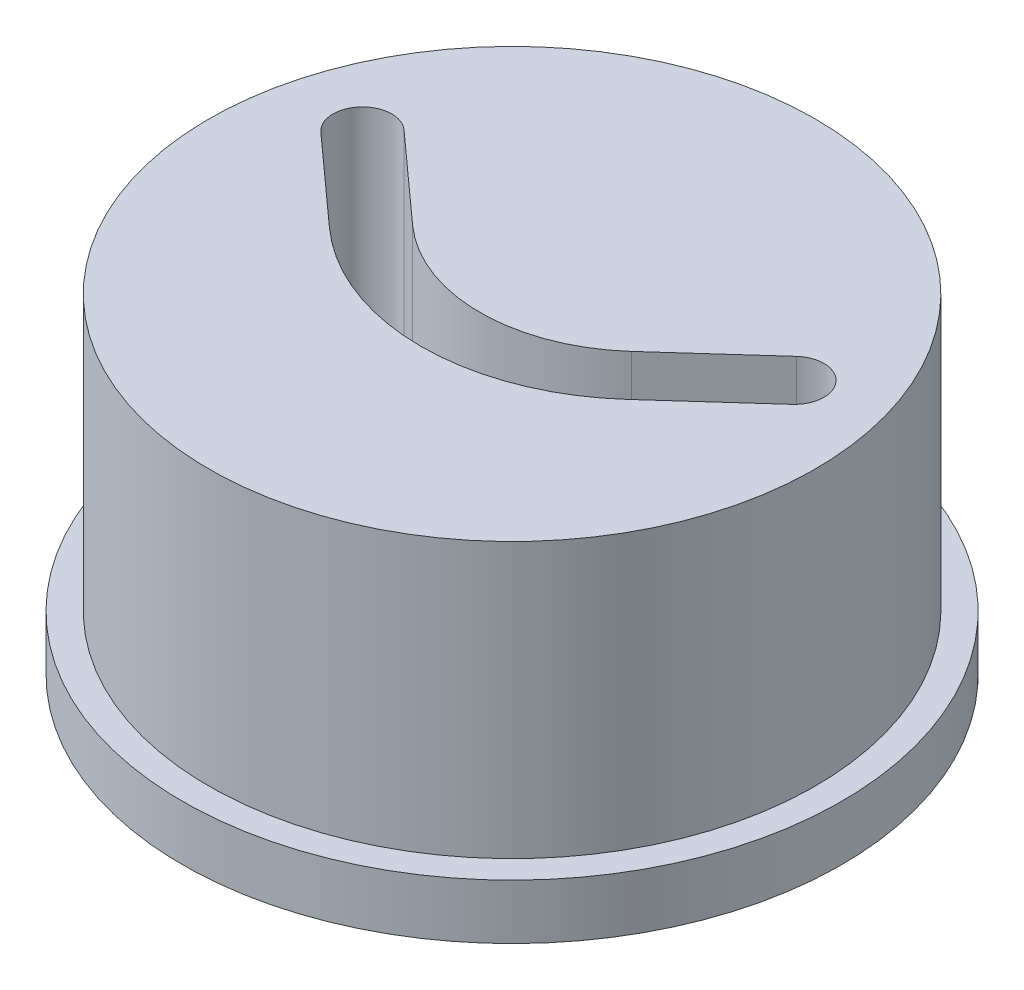
SolidWorks part; units mm, degrees
ref_plane "Front Plane" through (0, 0, 0) normal (0, 0, 1) x (1, 0, 0)
ref_plane "Top Plane" through (0, 0, 0) normal (0, 1, 0) x (1, 0, 0)
ref_plane "Right Plane" through (0, 0, 0) normal (1, 0, 0) x (0, 0, -1)
sketch "Sketch2" plane through (0, 0, 0) normal (0, 1, 0) x (1, 0, 0)
  line L0 (-6.985, 0) -> (6.985, 0) construction
  line L10 (0, 6.985) -> (0, -6.985) construction
  line L13 (0, -6.985) -> (0, 0) construction
  line L14 (-13.081, 3.175) -> (13.081, 3.175) construction
  line L15 (0, -4.445) -> (0, 3.175) construction
  line L16 (-13.081, 3.175) -> (-8.0591, -1.3498)
  line L17 (13.081, 3.175) -> (8.0591, -1.3498)
  line L18 (-11.8908, 4.4959) -> (-6.8689, -0.0289)
  line L19 (11.8908, 4.4959) -> (6.8689, -0.0289)
  line L21 (-12.4859, 3.8355) -> (12.4859, 3.8355) construction
  circle A0 centre (0, 0) radius 17.526
  arc A9 (-8.0591, -1.3498) -> (8.0591, -1.3498) centre (0, 7.5946) ccw
  arc A10 (-13.081, 3.175) -> (-11.8908, 4.4959) centre (-12.4859, 3.8355) cw
  arc A11 (-6.8689, -0.0289) -> (6.8689, -0.0289) centre (0, 7.5946) ccw
  arc A12 (11.8908, 4.4959) -> (13.081, 3.175) centre (12.4859, 3.8355) cw
  point P13 (12.2811, 12.5034)
  point P36 (0, 3.175)
  point P37 (-33.8663, 15.7634)
  point P42 (0, -4.445)
  point P47 (0, 3.175)
  dimension "D1" = 35.052
  dimension "D4" = 24.9718
  dimension "D9" = 12.0396
  dimension "D11" = 0.889
  dimension "D12" = 10.2616
  dimension "D3" = 3.175
  dimension "D10" = 6.7597
extrude "Boss-Extrude1" add sketch "Sketch2" along normal blind 19.05
sketch "Sketch14" plane through (0, 19.05, 0) normal (0, 1, 0) x (1, 0, 0)
  line L37 (8.6032, -1.9537) -> (13.6251, 2.5712)
  line L38 (11.3468, 5.0997) -> (6.3249, 0.5749)
  line L39 (-6.3249, 0.5749) -> (-11.3468, 5.0997)
  line L40 (-13.6251, 2.5712) -> (-8.6032, -1.9537)
  line L41 (8.6032, -1.9537) -> (13.6251, 2.5712)
  line L42 (11.3468, 5.0997) -> (6.3249, 0.5749)
  line L43 (-6.3249, 0.5749) -> (-11.3468, 5.0997)
  line L44 (-13.6251, 2.5712) -> (-8.6032, -1.9537)
  arc A43 (13.6251, 2.5712) -> (11.3468, 5.0997) centre (12.4859, 3.8355) ccw
  arc A44 (-6.3249, 0.5749) -> (6.3249, 0.5749) centre (0, 7.5946) ccw
  arc A45 (-11.3468, 5.0997) -> (-13.6251, 2.5712) centre (-12.4859, 3.8355) ccw
  arc A46 (-8.6032, -1.9537) -> (8.6032, -1.9537) centre (0, 7.5946) ccw
  arc A47 (13.6251, 2.5712) -> (11.3468, 5.0997) centre (12.4859, 3.8355) ccw
  arc A48 (-6.3249, 0.5749) -> (6.3249, 0.5749) centre (0, 7.5946) ccw
  arc A49 (-11.3468, 5.0997) -> (-13.6251, 2.5712) centre (-12.4859, 3.8355) ccw
  arc A50 (-8.6032, -1.9537) -> (8.6032, -1.9537) centre (0, 7.5946) ccw
  dimension "D1" = 0.8128
sketch "Sketch15" plane through (0, 0, 0) normal (0, -1, 0) x (1, 0, 0)
  line L0 (-13.081, -3.175) -> (-8.0591, 1.3498) construction
  line L1 (-6.8689, 0.0289) -> (-11.8908, -4.4959) construction
  line L2 (11.8908, -4.4959) -> (6.8689, 0.0289) construction
  line L3 (8.0591, 1.3498) -> (13.081, -3.175) construction
  line L4 (-13.081, -3.175) -> (-8.0591, 1.3498)
  line L5 (-6.8689, 0.0289) -> (-11.8908, -4.4959)
  line L6 (11.8908, -4.4959) -> (6.8689, 0.0289)
  line L7 (8.0591, 1.3498) -> (13.081, -3.175)
  circle A0 centre (0, 0) radius 19.05
  arc A1 (8.0591, 1.3498) -> (-8.0591, 1.3498) centre (0, -7.5946) ccw construction
  arc A2 (-13.081, -3.175) -> (-11.8908, -4.4959) centre (-12.4859, -3.8355) ccw construction
  arc A3 (6.8689, 0.0289) -> (-6.8689, 0.0289) centre (0, -7.5946) ccw construction
  arc A4 (11.8908, -4.4959) -> (13.081, -3.175) centre (12.4859, -3.8355) ccw construction
  arc A5 (8.0591, 1.3498) -> (-8.0591, 1.3498) centre (0, -7.5946) ccw
  arc A6 (-13.081, -3.175) -> (-11.8908, -4.4959) centre (-12.4859, -3.8355) ccw
  arc A7 (6.8689, 0.0289) -> (-6.8689, 0.0289) centre (0, -7.5946) ccw
  arc A8 (11.8908, -4.4959) -> (13.081, -3.175) centre (12.4859, -3.8355) ccw
  dimension "D1" = 38.1
extrude "Boss-Extrude2" add sketch "Sketch15" against normal blind 3.175
extrude "Cut-Extrude2" cut sketch "Sketch14" against normal blind 12.7
